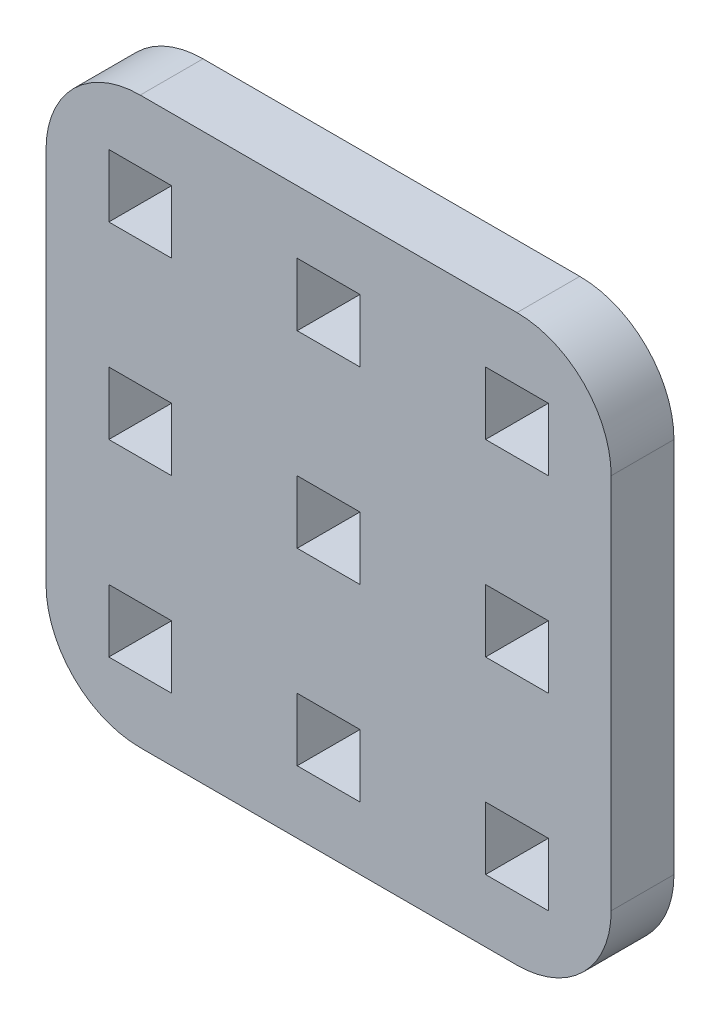
SolidWorks part; units mm, degrees
ref_plane "Alzado" through (0, 0, 0) normal (0, 0, 1) x (1, 0, 0)
ref_plane "Planta" through (0, 0, 0) normal (0, 1, 0) x (1, 0, 0)
ref_plane "Vista lateral" through (0, 0, 0) normal (1, 0, 0) x (0, 0, -1)
sketch "Model" plane through (0, 0, 0) normal (0, 0, 1) x (1, 0, 0)
  line L0 (11.3955, 295.2597) -> (11.3955, 292.2597)
  line L1 (14.3955, 295.2597) -> (11.3955, 295.2597)
  line L2 (14.3955, 292.2597) -> (14.3955, 295.2597)
  line L3 (11.3955, 292.2597) -> (14.3955, 292.2597)
  line L4 (20.3955, 295.2597) -> (20.3955, 292.2597)
  line L5 (23.3955, 295.2597) -> (20.3955, 295.2597)
  line L6 (23.3955, 292.2597) -> (23.3955, 295.2597)
  line L7 (20.3955, 292.2597) -> (23.3955, 292.2597)
  line L8 (29.3955, 295.2597) -> (29.3955, 292.2597)
  line L9 (32.3955, 295.2597) -> (29.3955, 295.2597)
  line L10 (32.3955, 292.2597) -> (32.3955, 295.2597)
  line L11 (29.3955, 292.2597) -> (32.3955, 292.2597)
  line L12 (11.3955, 277.2597) -> (11.3955, 274.2597)
  line L13 (14.3955, 277.2597) -> (11.3955, 277.2597)
  line L14 (14.3955, 274.2597) -> (14.3955, 277.2597)
  line L15 (11.3955, 274.2597) -> (14.3955, 274.2597)
  line L16 (20.3955, 277.2597) -> (20.3955, 274.2597)
  line L17 (23.3955, 277.2597) -> (20.3955, 277.2597)
  line L18 (23.3955, 274.2597) -> (23.3955, 277.2597)
  line L19 (20.3955, 274.2597) -> (23.3955, 274.2597)
  line L20 (29.3955, 277.2597) -> (29.3955, 274.2597)
  line L21 (32.3955, 277.2597) -> (29.3955, 277.2597)
  line L22 (32.3955, 274.2597) -> (32.3955, 277.2597)
  line L23 (29.3955, 274.2597) -> (32.3955, 274.2597)
  line L24 (11.3955, 286.2597) -> (11.3955, 283.2597)
  line L25 (14.3955, 286.2597) -> (11.3955, 286.2597)
  line L26 (14.3955, 283.2597) -> (14.3955, 286.2597)
  line L27 (11.3955, 283.2597) -> (14.3955, 283.2597)
  line L28 (20.3955, 286.2597) -> (20.3955, 283.2597)
  line L29 (23.3955, 286.2597) -> (20.3955, 286.2597)
  line L30 (23.3955, 283.2597) -> (23.3955, 286.2597)
  line L31 (20.3955, 283.2597) -> (23.3955, 283.2597)
  line L32 (29.3955, 286.2597) -> (29.3955, 283.2597)
  line L33 (32.3955, 286.2597) -> (29.3955, 286.2597)
  line L34 (32.3955, 283.2597) -> (32.3955, 286.2597)
  line L35 (29.3955, 283.2597) -> (32.3955, 283.2597)
  line L36 (12.8955, 298.2597) -> (30.8955, 298.2597)
  line L37 (12.8955, 271.2597) -> (30.8955, 271.2597)
  line L38 (8.3955, 293.7597) -> (8.3955, 275.7597)
  line L39 (35.3955, 293.7597) -> (35.3955, 275.7597)
  arc A0 (35.3955, 293.7597) -> (30.8955, 298.2597) centre (30.8955, 293.7597) ccw
  arc A1 (30.8955, 271.2597) -> (35.3955, 275.7597) centre (30.8955, 275.7597) ccw
  arc A2 (12.8955, 298.2597) -> (8.3955, 293.7597) centre (12.8955, 293.7597) ccw
  arc A3 (8.3955, 275.7597) -> (12.8955, 271.2597) centre (12.8955, 275.7597) ccw
extrude "Saliente-Extruir1" add sketch "Model" along normal blind 3
